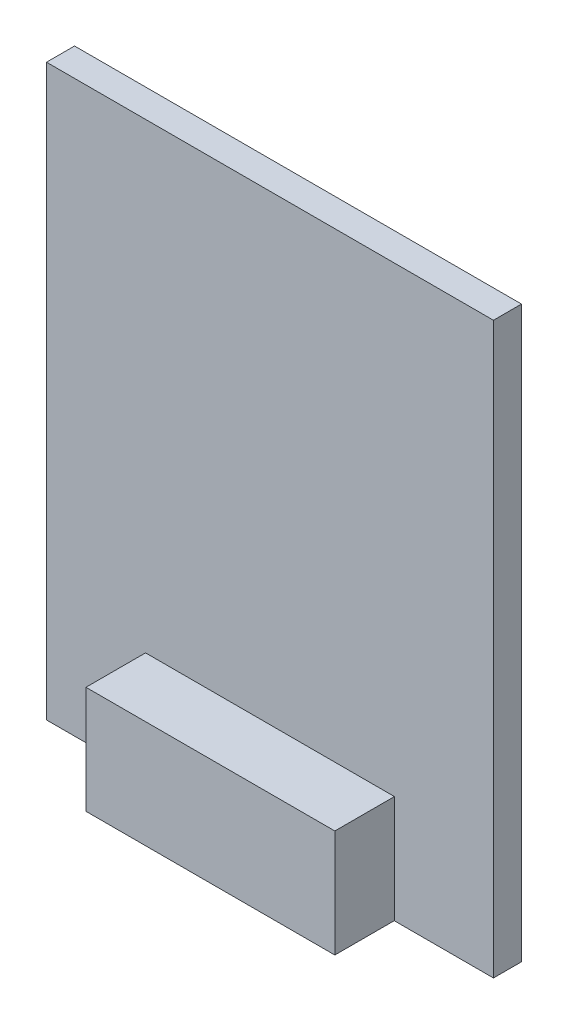
SolidWorks part; units mm, degrees
ref_plane "前视基准面" through (0, 0, 0) normal (0, 0, 1) x (1, 0, 0)
ref_plane "上视基准面" through (0, 0, 0) normal (0, 1, 0) x (1, 0, 0)
ref_plane "右视基准面" through (0, 0, 0) normal (1, 0, 0) x (0, 0, -1)
other "Configuration Table"
sketch "草图1" plane through (0, 0, 0) normal (0, 0, 1) x (1, 0, 0)
  line L1 (-12.75, 16.25) -> (12.75, 16.25)
  line L2 (-12.75, 16.25) -> (-12.75, -16.25)
  line L3 (-12.75, -16.25) -> (12.75, -16.25)
  line L4 (12.75, 16.25) -> (12.75, -16.25)
  line L5 (-12.75, 16.25) -> (12.75, -16.25) construction
  line L6 (-12.75, -16.25) -> (12.75, 16.25) construction
  point P0 (0, 0)
  dimension "D1" = 32.5
  dimension "D2" = 25.5
extrude "凸台-拉伸1" add sketch "草图1" along normal blind 1.6
sketch "草图2" plane through (0, 0, 0) normal (0, 0, 1) x (1, 0, 0)
  line L0 (-12.75, -16.25) -> (12.75, -16.25) construction
  line L6 (12.75, -16.25) -> (12.75, 16.25) construction
  line L7 (-7.1, -10.11) -> (7.1, -10.11)
  line L8 (-7.1, -10.11) -> (-7.1, -16.24)
  line L9 (-7.1, -16.24) -> (7.1, -16.24)
  line L10 (7.1, -10.11) -> (7.1, -16.24)
  dimension "D1" = 14.2
  dimension "D2" = 6.13
  dimension "D3" = 0.01
  dimension "D4" = 5.65
extrude "凸台-拉伸3" add sketch "草图2" along normal blind 5
